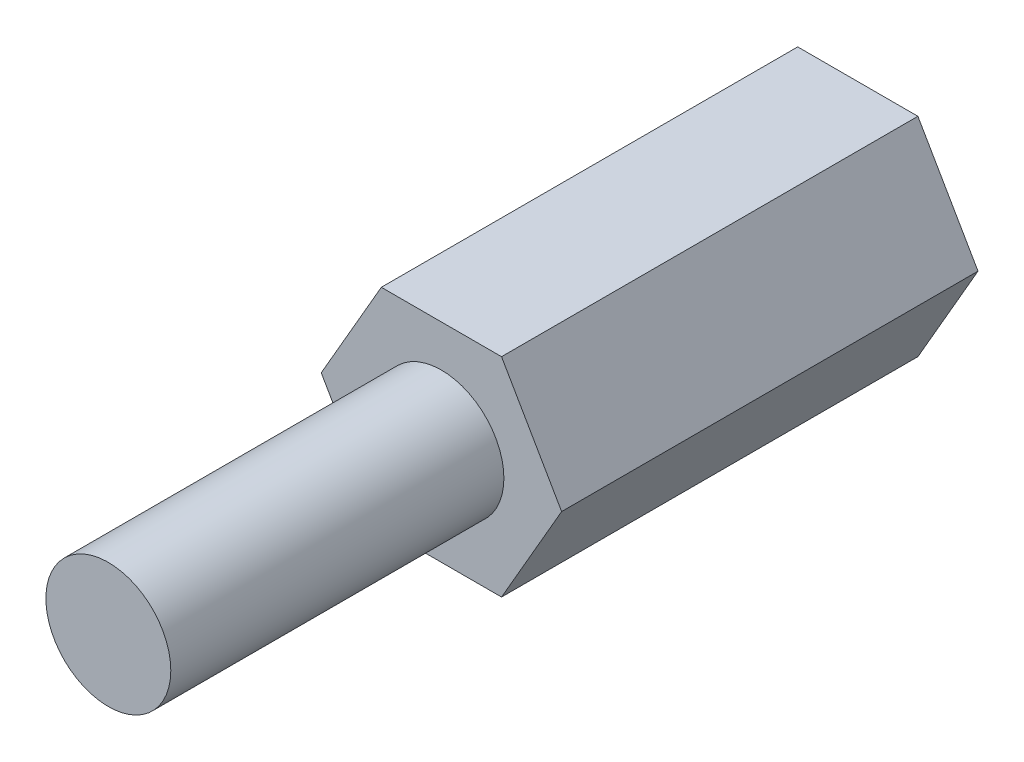
SolidWorks part; units mm, degrees
ref_plane "Plan de face" through (0, 0, 0) normal (0, 0, 1) x (1, 0, 0)
ref_plane "Plan de dessus" through (0, 0, 0) normal (0, 1, 0) x (1, 0, 0)
ref_plane "Plan de droite" through (0, 0, 0) normal (1, 0, 0) x (0, 0, -1)
sketch "Esquisse1" plane through (0, 0, 0) normal (0, 0, 1) x (1, 0, 0)
  line L1 (2.8868, 0) -> (1.4434, 2.5)
  line L2 (1.4434, 2.5) -> (-1.4434, 2.5)
  line L3 (-1.4434, 2.5) -> (-2.8868, 0)
  line L4 (-2.8868, 0) -> (-1.4434, -2.5)
  line L5 (-1.4434, -2.5) -> (1.4434, -2.5)
  line L6 (1.4434, -2.5) -> (2.8868, 0)
  circle A0 centre (0, 0) radius 2.5 construction
  dimension "D1" = 5
extrude "Boss.-Extru.1" add sketch "Esquisse1" along normal blind 10
sketch "Esquisse2" plane through (0, 0, 10) normal (0, 0, 1) x (1, 0, 0)
  circle A0 centre (0, 0) radius 1.5
  dimension "D1" = 3
extrude "Boss.-Extru.2" add sketch "Esquisse2" along normal blind 8
sketch "Esquisse3" plane through (0, 0, 0) normal (0, 0, -1) x (-1, 0, 0)
  circle A0 centre (0, 0) radius 1.5
  dimension "D1" = 3
extrude "Enlèv. mat.-Extru.1" cut sketch "Esquisse3" against normal blind 8
